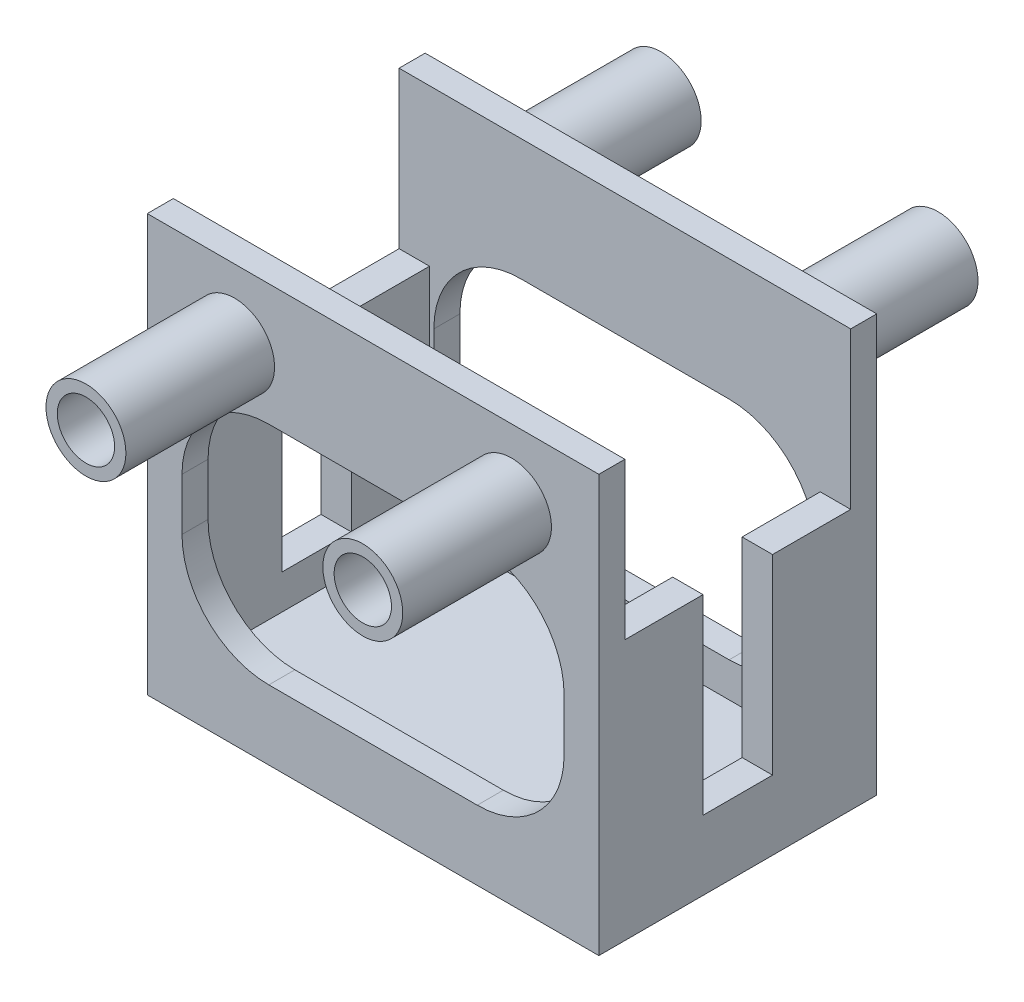
SolidWorks part; units mm, degrees
ref_plane "Front Plane" through (0, 0, 0) normal (0, 0, 1) x (1, 0, 0)
ref_plane "Top Plane" through (0, 0, 0) normal (0, 1, 0) x (1, 0, 0)
ref_plane "Right Plane" through (0, 0, 0) normal (1, 0, 0) x (0, 0, -1)
sketch "Sketch2" plane through (0, 0, 0) normal (0, 1, 0) x (1, 0, 0)
  line L0 (0, 0) -> (26, 0)
  line L1 (26, 0) -> (26, 16)
  line L2 (26, 16) -> (0, 16)
  line L3 (0, 16) -> (0, 0)
  dimension "D1" = 16
  dimension "D2" = 26
extrude "Boss-Extrude1" add sketch "Sketch2" along normal blind 2
sketch "Sketch3" plane through (0, 2, 0) normal (0, 1, 0) x (1, 0, 0)
  line L0 (0, 16) -> (0, 0)
  line L1 (0, 0) -> (26, 0)
  line L2 (26, 0) -> (26, 16)
  line L3 (26, 16) -> (0, 16)
  line L4 (1.75, 14.5) -> (1.75, 1.5)
  line L5 (1.75, 1.5) -> (24.25, 1.5)
  line L6 (24.25, 1.5) -> (24.25, 14.5)
  line L7 (24.25, 14.5) -> (1.75, 14.5)
  dimension "D1" = 13
  dimension "D2" = 22.5
  dimension "D3" = 1.75
  dimension "D4" = 1.5
extrude "Boss-Extrude2" add sketch "Sketch3" along normal blind 22
sketch "Sketch6" plane through (0, 0, 0) normal (-1, 0, 0) x (0, 0, 1)
  line L0 (-14.5, 24) -> (-14.5, 15)
  line L1 (-16, 24) -> (0, 24) construction
  line L2 (-14.5, 15) -> (-10, 15)
  line L3 (-1.5, 15) -> (-1.5, 24)
  line L4 (-1.5, 24) -> (-14.5, 24)
  line L5 (-16, 24) -> (-16, 0) construction
  line L6 (0, 24) -> (0, 0) construction
  line L7 (-16, 0) -> (0, 0) construction
  line L8 (-10, 15) -> (-10, 4)
  line L9 (-10, 4) -> (-6, 4)
  line L10 (-6, 4) -> (-6, 15)
  line L11 (-6, 15) -> (-1.5, 15)
  dimension "D1" = 1.5
  dimension "D2" = 1.5
  dimension "D3" = 15
  dimension "D4" = 4
  dimension "D5" = 6
  dimension "D6" = 4
extrude "Cut-Extrude1" cut sketch "Sketch6" against normal up to next
sketch "Sketch7" plane through (26, 0, 0) normal (1, 0, 0) x (0, 0, -1)
  line L0 (1.5, 24) -> (1.5, 15)
  line L1 (0, 24) -> (16, 24) construction
  line L2 (1.5, 15) -> (6, 15)
  line L3 (6, 15) -> (6, 4)
  line L4 (6, 4) -> (10, 4)
  line L5 (10, 4) -> (10, 15)
  line L6 (10, 15) -> (14.5, 15)
  line L7 (14.5, 15) -> (14.5, 24)
  line L8 (14.5, 24) -> (1.5, 24)
  line L10 (16, 24) -> (16, 0) construction
  dimension "D5" = 6
extrude "Cut-Extrude2" cut sketch "Sketch7" against normal up to next
sketch "Sketch8" plane through (0, 0, -16) normal (0, 0, -1) x (-1, 0, 0)
  line L0 (-24, 12) -> (-24, 9)
  line L1 (-19, 4) -> (-7, 4)
  line L2 (-2, 9) -> (-2, 12)
  line L3 (-7, 17) -> (-19, 17)
  line L4 (-26, 24) -> (0, 24) construction
  line L5 (-26, 24) -> (-26, 0) construction
  line L6 (0, 24) -> (0, 0) construction
  line L7 (-26, 0) -> (0, 0) construction
  arc A0 (-24, 12) -> (-19, 17) centre (-19, 12) cw
  arc A1 (-2, 12) -> (-7, 17) centre (-7, 12) ccw
  arc A2 (-7, 4) -> (-2, 9) centre (-7, 9) ccw
  arc A3 (-24, 9) -> (-19, 4) centre (-19, 9) ccw
  dimension "D5" = 5
  dimension "D6" = 5
  dimension "D7" = 5
  dimension "D8" = 5
  dimension "D1" = 7
  dimension "D2" = 2
  dimension "D3" = 2
  dimension "D4" = 4
extrude "Cut-Extrude3" cut sketch "Sketch8" against normal up to next
sketch "Sketch9" plane through (0, 0, 0) normal (0, 0, 1) x (1, 0, 0)
  line L0 (2, 12) -> (2, 9)
  line L1 (7, 4) -> (19, 4)
  line L2 (24, 9) -> (24, 12)
  line L3 (19, 17) -> (7, 17)
  line L4 (0, 24) -> (26, 24) construction
  line L5 (0, 24) -> (0, 0) construction
  line L6 (26, 24) -> (26, 0) construction
  line L7 (0, 0) -> (26, 0) construction
  arc A0 (2, 12) -> (7, 17) centre (7, 12) cw
  arc A1 (24, 12) -> (19, 17) centre (19, 12) ccw
  arc A2 (19, 4) -> (24, 9) centre (19, 9) ccw
  arc A3 (2, 9) -> (7, 4) centre (7, 9) ccw
  dimension "D5" = 5
  dimension "D6" = 5
  dimension "D7" = 5
  dimension "D8" = 5
  dimension "D1" = 7
  dimension "D2" = 2
  dimension "D3" = 2
  dimension "D4" = 4
extrude "Cut-Extrude4" cut sketch "Sketch9" against normal up to next
sketch "Sketch10" plane through (0, 0, -16) normal (0, 0, -1) x (-1, 0, 0)
  line L0 (-26, 24) -> (-26, 0) construction
  line L2 (-26, 24) -> (0, 24) construction
  circle A0 centre (-20.97, 20) radius 2.3
  circle A1 centre (-5.03, 20) radius 2.3
  dimension "D1" = 4.6
  dimension "D2" = 4.6
  dimension "D3" = 15.94
  dimension "D4" = 5.03
  dimension "D5" = 4
extrude "Boss-Extrude3" add sketch "Sketch10" along normal blind 8.56
sketch "Sketch11" plane through (0, 0, 0) normal (0, 0, 1) x (1, 0, 0)
  line L0 (0, 24) -> (0, 0) construction
  line L2 (0, 24) -> (26, 24) construction
  circle A0 centre (5.03, 20) radius 2.3
  circle A1 centre (20.97, 20) radius 2.3
  dimension "D1" = 4.6
  dimension "D2" = 4.6
  dimension "D3" = 5.03
  dimension "D4" = 4
  dimension "D5" = 4
  dimension "D6" = 15.94
extrude "Boss-Extrude4" add sketch "Sketch11" along normal blind 8.56
sketch "Sketch12" plane through (0, 0, -24.56) normal (0, 0, -1) x (-1, 0, 0)
  circle A0 centre (-20.97, 20) radius 1.65
  circle A1 centre (-5.03, 20) radius 1.65
  dimension "D1" = 3.3
  dimension "D2" = 3.3
extrude "Cut-Extrude5" cut sketch "Sketch12" against normal blind 8.56
sketch "Sketch13" plane through (0, 0, 8.56) normal (0, 0, 1) x (1, 0, 0)
  circle A0 centre (5.03, 20) radius 1.65
  circle A1 centre (20.97, 20) radius 1.65
  dimension "D1" = 3.3
  dimension "D2" = 3.3
extrude "Cut-Extrude6" cut sketch "Sketch13" against normal blind 8.56
